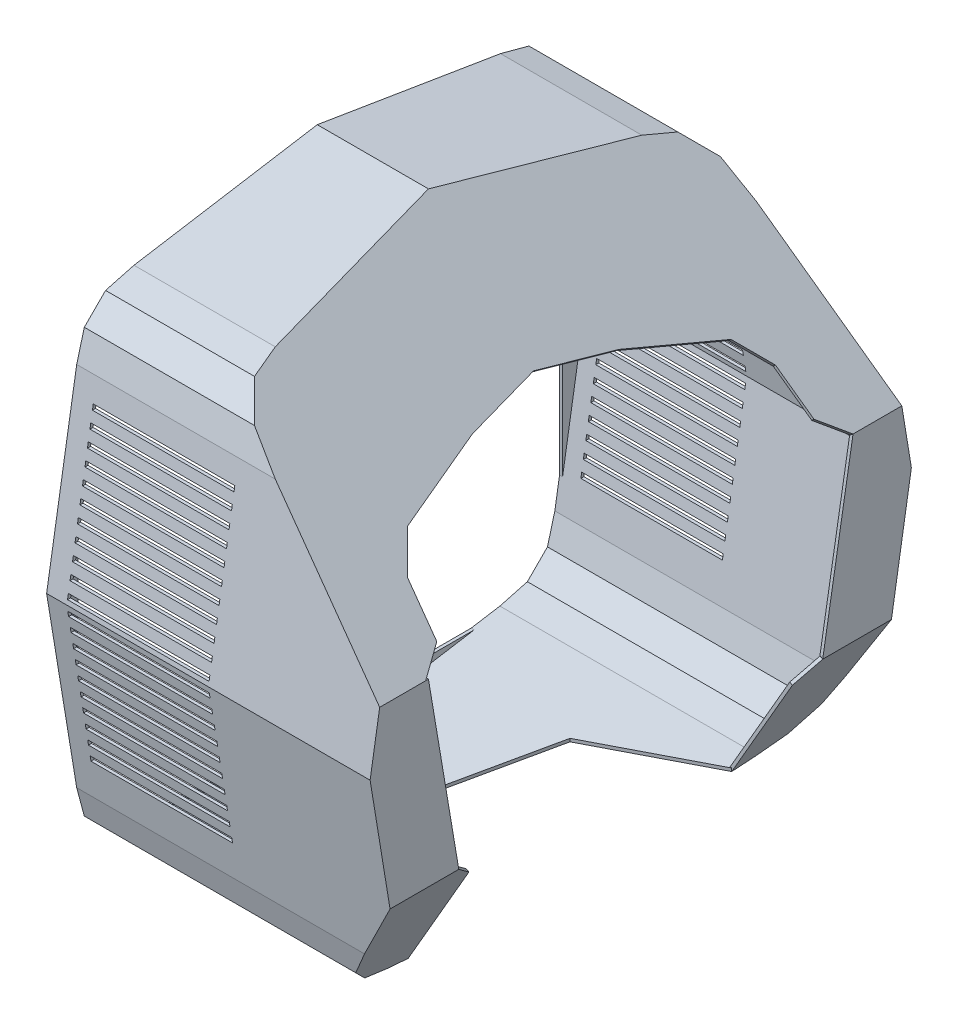
SolidWorks part; units mm, degrees
ref_plane "Plan de face" through (0, 0, 0) normal (0, 0, 1) x (1, 0, 0)
ref_plane "Plan de dessus" through (0, 0, 0) normal (0, 1, 0) x (1, 0, 0)
ref_plane "Plan de droite" through (0, 0, 0) normal (1, 0, 0) x (0, 0, -1)
sketch "Esquisse1" plane through (0, 0, 0) normal (1, 0, 0) x (0, 0, -1)
  line L0 (0, 0) -> (-210, 0) construction
  line L1 (0, 0) -> (0, -210) construction
  line L2 (40, -130) -> (40, -126.3181)
  line L3 (-40, -130) -> (40, -130) construction
  line L4 (-40, -130) -> (-40, -170)
  line L5 (-40, -170) -> (40, -170)
  line L6 (40, -130) -> (40, -170)
  line L7 (-40, -130) -> (-40, -126.3181)
  line L8 (40, 130) -> (40, 126.3181)
  line L9 (-40, 130) -> (-40, 126.3181)
  line L10 (-40, 130) -> (-40, 170)
  line L11 (-40, 130) -> (40, 130) construction
  line L12 (40, 130) -> (40, 170)
  line L13 (-40, 170) -> (40, 170)
  circle A0 centre (0, 0) radius 210
  circle A1 centre (0, 0) radius 147.5 construction
  circle A2 centre (-147.5, 0) radius 6.75
  arc A3 (40, -126.3181) -> (40, 126.3181) centre (0, 0) ccw
  circle A4 centre (-142.0303, 39.795) radius 6.75
  circle A5 centre (-126.0269, 76.6386) radius 6.75
  circle A6 centre (-100.6766, 107.7983) radius 6.75
  circle A7 centre (-67.8596, 130.9631) radius 6.75
  circle A8 centre (-30.0098, 144.4149) radius 6.75 construction
  circle A9 centre (10.0658, 147.1561) radius 6.75 construction
  circle A10 centre (49.3947, 138.9835) radius 6.75
  circle A11 centre (85.0603, 120.5031) radius 6.75
  circle A12 centre (114.4174, 93.0855) radius 6.75
  circle A13 centre (135.2887, 58.7642) radius 6.75
  circle A14 centre (146.1262, 20.0846) radius 6.75
  circle A15 centre (146.1262, -20.0846) radius 6.75
  circle A16 centre (135.2887, -58.7642) radius 6.75
  circle A17 centre (114.4174, -93.0855) radius 6.75
  circle A18 centre (85.0603, -120.5031) radius 6.75
  circle A19 centre (49.3947, -138.9835) radius 6.75
  circle A20 centre (10.0658, -147.1561) radius 6.75 construction
  circle A21 centre (-30.0098, -144.4149) radius 6.75 construction
  circle A22 centre (-67.8596, -130.9631) radius 6.75
  circle A23 centre (-100.6766, -107.7983) radius 6.75
  circle A24 centre (-126.0269, -76.6386) radius 6.75
  circle A25 centre (-142.0303, -39.795) radius 6.75
  arc A28 (-40, 126.3181) -> (-40, -126.3181) centre (0, 0) ccw
  point P55 (0, 0)
  point P59 (0, -130)
  point P60 (-130, 0)
  dimension "D1" = 147.5
  dimension "D2" = 13.5
  dimension "D3" = 265
  dimension "D5" = 420
  dimension "D6" = 40
  dimension "D9" = 132.5
  dimension "D7" = 80
  dimension "D8" = 130
  dimension "D4" = 23
extrude "Boss.-Extru.1" add sketch "Esquisse1" along normal blind 10
sketch "Esquisse2" plane through (0, 0, 0) normal (-1, 0, 0) x (0, 0, 1)
  line L0 (-180.6658, -180.6658) -> (-218.1424, -143.1891) construction
  line L1 (-180.6658, -180.6658) -> (-210.0107, -210.0107) construction
  line L2 (0, 0) -> (0, -255.5) construction
  line L3 (0, 0) -> (-180.6658, -180.6658) construction
  line L4 (-80.9762, -193.7598) -> (-127.4885, -240.2721)
  line L5 (240.2721, -127.4885) -> (269.6802, -156.8967)
  line L6 (-240.2721, -127.4885) -> (-193.7598, -80.9762)
  line L7 (-220.6173, -220.6173) -> (-210.0107, -210.0107) construction
  line L8 (-127.4885, 240.2721) -> (-80.9762, 193.7598)
  line L9 (240.2721, 127.4885) -> (269.6802, 156.8967)
  line L10 (-193.7598, 80.9762) -> (-240.2721, 127.4885)
  line L11 (240.2721, 127.4885) -> (193.7598, 80.9762)
  line L12 (127.4885, 240.2721) -> (156.8967, 269.6802)
  line L13 (80.9762, 193.7598) -> (127.4885, 240.2721)
  line L14 (127.4885, -240.2721) -> (80.3433, -193.1268)
  line L15 (127.4885, -240.2721) -> (156.8967, -269.6802)
  line L16 (193.7598, -80.9762) -> (240.2721, -127.4885)
  line L17 (-127.4885, 240.2721) -> (-156.8967, 269.6802)
  line L18 (-240.2721, 127.4885) -> (-269.6802, 156.8967)
  line L19 (-127.4885, -240.2721) -> (-156.8967, -269.6802)
  line L20 (-240.2721, -127.4885) -> (-269.6802, -156.8967)
  circle A0 centre (0, 0) radius 213 construction
  circle A1 centre (0, 0) radius 255.5 construction
  circle A2 centre (-180.6658, -180.6658) radius 42.5 construction
  circle A3 centre (-180.6658, -180.6658) radius 41.5
  circle A4 centre (-218.1424, -143.1891) radius 6.75
  circle A5 centre (-143.1891, -218.1424) radius 6.75
  circle A6 centre (0, 0) radius 210 construction
  arc A7 (-80.9762, -193.7598) -> (-193.7598, -80.9762) centre (0, 0) cw
  arc A8 (-193.7598, 80.9762) -> (-80.9762, 193.7598) centre (0, 0) cw
  circle A9 centre (-218.1424, 143.1891) radius 6.75
  circle A10 centre (-180.6658, 180.6658) radius 41.5
  circle A11 centre (-143.1891, 218.1424) radius 6.75
  arc A12 (80.9762, 193.7598) -> (193.7598, 80.9762) centre (0, 0) cw
  circle A13 centre (143.1891, 218.1424) radius 6.75
  circle A14 centre (180.6658, 180.6658) radius 41.5
  circle A15 centre (218.1424, 143.1891) radius 6.75
  arc A16 (193.7598, -80.9762) -> (80.9762, -193.7598) centre (0, 0) cw
  circle A17 centre (218.1424, -143.1891) radius 6.75
  circle A18 centre (180.6658, -180.6658) radius 41.5
  circle A19 centre (143.1891, -218.1424) radius 6.75
  circle A20 centre (0, 0) radius 312 construction
  arc A21 (240.2721, -127.4885) -> (240.2721, 127.4885) centre (0, 0) ccw construction
  arc A22 (-240.2721, 127.4885) -> (-240.2721, -127.4885) centre (0, 0) ccw construction
  arc A23 (127.4885, 240.2721) -> (-127.4885, 240.2721) centre (0, 0) ccw construction
  arc A24 (156.8967, -269.6802) -> (269.6802, -156.8967) centre (0, 0) ccw
  arc A25 (269.6802, 156.8967) -> (156.8967, 269.6802) centre (0, 0) ccw
  arc A26 (-127.4885, -240.2721) -> (127.4885, -240.2721) centre (0, 0) ccw construction
  arc A27 (-156.8967, 269.6802) -> (-269.6802, 156.8967) centre (0, 0) ccw
  arc A28 (-156.8967, -269.6802) -> (-269.6802, -156.8967) centre (0, 0) cw
  point P57 (0, 0)
  circle M11 centre (0, 0) radius 210
  dimension "D1" = 426
  dimension "D2" = 85
  dimension "D3" = 83
  dimension "D4" = 13.5
  dimension "D10" = 40
  dimension "D7" = 624
  dimension "D5" = 53
  dimension "D6" = 45
  dimension "D8" = 26.75
  dimension "D11" = 159.5
  dimension "D9" = 4
extrude "Boss.-Extru.2" add sketch "Esquisse2" against normal blind 10 contours A20 A26 L4 L6 A22 L10 L8 A23 L13 L11 A21 L16 L14 A17 A15 A14 A9 A3 A4 A5 A10 A11 A13 A18 A19 M11 | L9 A25 L12 L13 L11 A15 A14 A13 M11 | L17 A27 L18 L10 L8 A9 A10 A11 M11 | A28 L19 L4 L6 L20 A5 A4 A3 M11
sketch "Esquisse3" plane through (10, 0, 0) normal (1, 0, 0) x (0, 0, -1)
  line L0 (-156.8967, -269.6802) -> (156.8967, -269.6802)
  line L1 (156.8967, -269.6802) -> (126.8967, -239.6802)
  line L2 (-80.9762, -193.7598) -> (-156.8967, -269.6802) construction
  line L3 (126.8967, -239.6802) -> (-126.8967, -239.6802)
  line L4 (-193.7598, 80.9762) -> (-269.6802, 156.8967) construction
  line L5 (-126.8967, -239.6802) -> (-156.8967, -269.6802)
  line L6 (-269.6802, -156.8967) -> (-269.6802, 156.8967)
  line L7 (-269.6802, 156.8967) -> (-239.6802, 126.8967)
  line L8 (80.9762, 193.7598) -> (156.8967, 269.6802) construction
  line L9 (-239.6802, 126.8967) -> (-239.6802, -126.8967)
  line L11 (-239.6802, -126.8967) -> (-269.6802, -156.8967)
  line L12 (-156.8967, 269.6802) -> (156.8967, 269.6802)
  line L13 (156.8967, 269.6802) -> (126.8967, 239.6802)
  line L15 (126.8967, 239.6802) -> (-126.8967, 239.6802)
  line L17 (-126.8967, 239.6802) -> (-156.8967, 269.6802)
  line L18 (269.6802, 156.8967) -> (269.6802, -156.8967)
  line L19 (269.6802, -156.8967) -> (239.6802, -126.8967)
  line L21 (239.6802, -126.8967) -> (239.6802, 126.8967)
  line L23 (239.6802, 126.8967) -> (269.6802, 156.8967)
  line L24 (193.7598, 80.9762) -> (269.6802, 156.8967) construction
  dimension "D1" = 30
extrude "Boss.-Extru.3" add sketch "Esquisse3" against normal up to surface (10 mm away) up to face at (0, -76.6386, 119.2769)
fillet "Congé1" radius 20 16 edges at (5, -80.9762, 193.7598) (5, 193.7598, -80.9762) (5, -193.7598, 80.9762) (5, 80.9762, -193.7598) (5, -80.9762, -193.7598) (5, 80.9762, 193.7598) (5, -193.7598, -80.9762) (5, 193.7598, 80.9762) (5, -239.6802, 126.8967) (5, -239.6802, -126.8967) (5, -126.8967, -239.6802) (5, 126.8967, -239.6802) (5, 239.6802, -126.8967) (5, 239.6802, 126.8967) (5, 126.8967, 239.6802) (5, -126.8967, 239.6802)
sketch "Esquisse4" plane through (10, 0, 0) normal (1, 0, 0) x (0, 0, -1)
  line L0 (180.6658, 235.0178) -> (180.6658, 126.3138) construction
  line L1 (227.736, 207.8418) -> (207.8418, 227.736)
  line L2 (207.8418, 227.736) -> (180.6658, 235.0178)
  line L3 (180.6658, 235.0178) -> (153.4898, 227.736) construction
  line L4 (153.4898, 227.736) -> (133.5956, 207.8418) construction
  line L5 (133.5956, 207.8418) -> (126.3138, 180.6658) construction
  line L6 (126.3138, 180.6658) -> (133.5956, 153.4898) construction
  line L7 (133.5956, 153.4898) -> (153.4898, 133.5956) construction
  line L8 (153.4898, 133.5956) -> (180.6658, 126.3138) construction
  line L9 (180.6658, 126.3138) -> (207.8418, 133.5956) construction
  line L10 (207.8418, 133.5956) -> (227.736, 153.4898) construction
  line L11 (227.736, 153.4898) -> (235.0178, 180.6658) construction
  line L12 (235.0178, 180.6658) -> (227.736, 207.8418)
  line L13 (0, 0) -> (269.6802, 0) construction
  line L14 (269.6802, -156.8967) -> (269.6802, 156.8967) construction
  line L15 (0, 0) -> (0, 269.6802) construction
  line L16 (156.8967, 269.6802) -> (-156.8967, 269.6802) construction
  line L17 (180.6658, 235.0178) -> (0, 264.6802)
  line L18 (235.0178, 180.6658) -> (264.6802, 0)
  line L19 (180.6658, -235.0178) -> (0, -264.6802)
  line L20 (180.6658, -235.0178) -> (207.8418, -227.736)
  line L21 (207.8418, -227.736) -> (227.736, -207.8418)
  line L22 (227.736, -207.8418) -> (235.0178, -180.6658)
  line L23 (235.0178, -180.6658) -> (264.6802, 0)
  line L24 (-235.0178, -180.6658) -> (-264.6802, 0)
  line L25 (-235.0178, -180.6658) -> (-227.736, -207.8418)
  line L26 (-227.736, -207.8418) -> (-207.8418, -227.736)
  line L27 (-207.8418, -227.736) -> (-180.6658, -235.0178)
  line L28 (-180.6658, -235.0178) -> (0, -264.6802)
  line L29 (-180.6658, 235.0178) -> (0, 264.6802)
  line L30 (-180.6658, 235.0178) -> (-207.8418, 227.736)
  line L31 (-207.8418, 227.736) -> (-227.736, 207.8418)
  line L32 (-227.736, 207.8418) -> (-235.0178, 180.6658)
  line L33 (-235.0178, 180.6658) -> (-264.6802, 0)
  line L34 (-237.9541, -181.2986) -> (-267.7204, 0)
  line L35 (-237.9541, 181.2986) -> (-267.7204, 0)
  line L36 (-230.4257, 209.3947) -> (-237.9541, 181.2986)
  line L37 (-209.3947, 230.4257) -> (-230.4257, 209.3947)
  line L38 (-181.2986, 237.9541) -> (-209.3947, 230.4257)
  line L39 (-181.2986, 237.9541) -> (0, 267.7204)
  line L40 (181.2986, 237.9541) -> (0, 267.7204)
  line L41 (209.3947, 230.4257) -> (181.2986, 237.9541)
  line L42 (230.4257, 209.3947) -> (209.3947, 230.4257)
  line L43 (237.9541, 181.2986) -> (230.4257, 209.3947)
  line L44 (237.9541, 181.2986) -> (267.7204, 0)
  line L45 (237.9541, -181.2986) -> (267.7204, 0)
  line L46 (230.4257, -209.3947) -> (237.9541, -181.2986)
  line L47 (209.3947, -230.4257) -> (230.4257, -209.3947)
  line L48 (181.2986, -237.9541) -> (209.3947, -230.4257)
  line L49 (181.2986, -237.9541) -> (0, -267.7204)
  line L50 (-181.2986, -237.9541) -> (0, -267.7204)
  line L51 (-209.3947, -230.4257) -> (-181.2986, -237.9541)
  line L52 (-230.4257, -209.3947) -> (-209.3947, -230.4257)
  line L53 (-237.9541, -181.2986) -> (-230.4257, -209.3947)
  circle A0 centre (180.6658, 180.6658) radius 52.5 construction
  circle A1 centre (180.6658, -180.6658) radius 52.5 construction
  circle A2 centre (-180.6658, -180.6658) radius 52.5 construction
  circle A3 centre (-180.6658, 180.6658) radius 52.5 construction
  circle A4 centre (180.6658, 180.6658) radius 52.5 construction
  point P12 (0, 0)
  point P55 (0, 0)
  dimension "D1" = 105
  dimension "D3" = 5
  dimension "D4" = 5
  dimension "D6" = 3
  dimension "D2" = 4
  dimension "D5" = 4
extrude "Boss.-Extru.4" add sketch "Esquisse4" along normal blind 320
sketch "Esquisse5" plane through (10, 0, 0) normal (1, 0, 0) x (0, 0, -1)
  line L0 (-239.6802, 78.6124) -> (-239.6802, -78.6124)
  line L1 (-239.6802, -78.6124) -> (-239.6802, 78.6124) construction
  line L2 (-239.6802, -78.6124) -> (-239.6802, -152.2681)
  line L3 (-264.6802, 0) -> (-235.0178, -180.6658) construction
  line L4 (-239.6802, -152.2681) -> (-264.6802, 0)
  line L5 (-264.6802, 0) -> (-239.6802, 152.2681)
  line L6 (-235.0178, 180.6658) -> (-264.6802, 0) construction
  line L7 (-239.6802, 152.2681) -> (-239.6802, 78.6124)
  line L8 (78.6124, 239.6802) -> (-78.6124, 239.6802)
  line L9 (-78.6124, 239.6802) -> (-152.2681, 239.6802)
  line L10 (-152.2681, 239.6802) -> (0, 264.6802)
  line L11 (0, 264.6802) -> (152.2681, 239.6802)
  line L12 (152.2681, 239.6802) -> (78.6124, 239.6802)
  line L13 (239.6802, -78.6124) -> (239.6802, 78.6124)
  line L14 (239.6802, 78.6124) -> (239.6802, 152.2681)
  line L15 (239.6802, 152.2681) -> (264.6802, 0)
  line L16 (264.6802, 0) -> (239.6802, -152.2681)
  line L17 (239.6802, -152.2681) -> (239.6802, -78.6124)
  line L18 (-78.6124, -239.6802) -> (78.6124, -239.6802)
  line L19 (78.6124, -239.6802) -> (152.2681, -239.6802)
  line L20 (152.2681, -239.6802) -> (0, -264.6802)
  line L21 (0, -264.6802) -> (-152.2681, -239.6802)
  line L22 (-152.2681, -239.6802) -> (-78.6124, -239.6802)
  arc A0 (-239.6802, -78.6124) -> (-205.5381, -92.7546) centre (-219.6802, -78.6124) ccw construction
  point P34 (0, 0)
  dimension "D1" = 4
extrude "Boss.-Extru.5" add sketch "Esquisse5" along normal blind 3
sketch "Esquisse6" plane through (0, 269.6802, 0) normal (0, 1, 0) x (1, 0, 0)
  line L1 (-73.5539, 269.6802) -> (10, 269.6802)
  line L2 (-73.5539, 269.6802) -> (-73.5539, -269.6802)
  line L3 (-73.5539, -269.6802) -> (10, -269.6802)
  line L4 (10, 269.6802) -> (10, -269.6802)
extrude "Enlèv. mat.-Extru.1" cut sketch "Esquisse6" against normal through all
sketch "Esquisse7" plane through (0, 0, 0) normal (0, 1, 0) x (1, 0, 0)
  line L1 (260, 160) -> (146.8629, 113.1371)
  line L2 (146.8629, 113.1371) -> (100, 0)
  line L3 (100, 0) -> (146.8629, -113.1371)
  line L4 (146.8629, -113.1371) -> (260, -160)
  line L5 (260, -160) -> (373.1371, -113.1371) construction
  line L6 (373.1371, -113.1371) -> (420, 0) construction
  line L7 (420, 0) -> (373.1371, 113.1371) construction
  line L8 (373.1371, 113.1371) -> (260, 160) construction
  line L9 (100, 0) -> (420, 0) construction
  line L10 (260, 160) -> (420, 160)
  line L11 (420, 160) -> (420, 0)
  line L12 (420, 0) -> (420, -160)
  line L13 (420, -160) -> (260, -160)
  line L15 (260, 0) -> (0, 0) construction
  line L16 (330, 0) -> (330, -181.2986) construction
  circle A0 centre (260, 0) radius 147.8207 construction
  dimension "D1" = 160
  dimension "D2" = 90
extrude "Enlèv. mat.-Extru.2" cut sketch "Esquisse7" against normal through all
sketch "Esquisse8" plane through (0, 0, 0) normal (0, 0, 1) x (1, 0, 0)
  line L0 (170, 267.7204) -> (170, 159.2986) construction
  line L1 (170, 159.2986) -> (30, 159.2986)
  line L2 (170, 159.2986) -> (170, 154.2986)
  line L3 (170, 154.2986) -> (30, 154.2986)
  line L4 (30, 159.2986) -> (30, 154.2986)
  line L5 (330, 267.7204) -> (10, 267.7204) construction
  line L6 (30, 267.7204) -> (30, 159.2986) construction
  line L7 (330, 181.2986) -> (330, 0) construction
  line L8 (10, 181.2986) -> (10, 0) construction
  line L9 (330, 181.2986) -> (10, 181.2986) construction
  line L10 (170, 144.2986) -> (30, 144.2986)
  line L11 (170, 144.2986) -> (170, 139.2986)
  line L12 (170, 139.2986) -> (30, 139.2986)
  line L13 (30, 144.2986) -> (30, 139.2986)
  line L14 (170, 129.2986) -> (30, 129.2986)
  line L15 (170, 129.2986) -> (170, 124.2986)
  line L16 (170, 124.2986) -> (30, 124.2986)
  line L17 (30, 129.2986) -> (30, 124.2986)
  line L18 (170, 114.2986) -> (30, 114.2986)
  line L19 (170, 114.2986) -> (170, 109.2986)
  line L20 (170, 109.2986) -> (30, 109.2986)
  line L21 (30, 114.2986) -> (30, 109.2986)
  line L22 (170, 99.2986) -> (30, 99.2986)
  line L23 (170, 99.2986) -> (170, 94.2986)
  line L24 (170, 94.2986) -> (30, 94.2986)
  line L25 (30, 99.2986) -> (30, 94.2986)
  line L26 (170, 84.2986) -> (30, 84.2986)
  line L27 (170, 84.2986) -> (170, 79.2986)
  line L28 (170, 79.2986) -> (30, 79.2986)
  line L29 (30, 84.2986) -> (30, 79.2986)
  line L30 (170, 69.2986) -> (30, 69.2986)
  line L31 (170, 69.2986) -> (170, 64.2986)
  line L32 (170, 64.2986) -> (30, 64.2986)
  line L33 (30, 69.2986) -> (30, 64.2986)
  line L34 (170, 54.2986) -> (30, 54.2986)
  line L35 (170, 54.2986) -> (170, 49.2986)
  line L36 (170, 49.2986) -> (30, 49.2986)
  line L37 (30, 54.2986) -> (30, 49.2986)
  line L38 (170, 39.2986) -> (30, 39.2986)
  line L39 (170, 39.2986) -> (170, 34.2986)
  line L40 (170, 34.2986) -> (30, 34.2986)
  line L41 (30, 39.2986) -> (30, 34.2986)
  line L42 (170, 24.2986) -> (30, 24.2986)
  line L43 (170, 24.2986) -> (170, 19.2986)
  line L44 (170, 19.2986) -> (30, 19.2986)
  line L45 (30, 24.2986) -> (30, 19.2986)
  line L46 (170, 9.2986) -> (30, 9.2986)
  line L47 (170, 9.2986) -> (170, 4.2986)
  line L48 (170, 4.2986) -> (30, 4.2986)
  line L49 (30, 9.2986) -> (30, 4.2986)
  line L50 (170, -5.7014) -> (30, -5.7014)
  line L51 (170, -5.7014) -> (170, -10.7014)
  line L52 (170, -10.7014) -> (30, -10.7014)
  line L53 (30, -5.7014) -> (30, -10.7014)
  line L54 (170, -20.7014) -> (30, -20.7014)
  line L55 (170, -20.7014) -> (170, -25.7014)
  line L56 (170, -25.7014) -> (30, -25.7014)
  line L57 (30, -20.7014) -> (30, -25.7014)
  line L58 (170, -35.7014) -> (30, -35.7014)
  line L59 (170, -35.7014) -> (170, -40.7014)
  line L60 (170, -40.7014) -> (30, -40.7014)
  line L61 (30, -35.7014) -> (30, -40.7014)
  line L62 (170, -50.7014) -> (30, -50.7014)
  line L63 (170, -50.7014) -> (170, -55.7014)
  line L64 (170, -55.7014) -> (30, -55.7014)
  line L65 (30, -50.7014) -> (30, -55.7014)
  line L66 (170, -65.7014) -> (30, -65.7014)
  line L67 (170, -65.7014) -> (170, -70.7014)
  line L68 (170, -70.7014) -> (30, -70.7014)
  line L69 (30, -65.7014) -> (30, -70.7014)
  line L70 (30, 154.2986) -> (30, 144.2986) construction
  line L71 (170, -80.7014) -> (30, -80.7014)
  line L72 (170, -80.7014) -> (170, -85.7014)
  line L73 (170, -85.7014) -> (30, -85.7014)
  line L74 (30, -80.7014) -> (30, -85.7014)
  line L75 (170, -95.7014) -> (30, -95.7014)
  line L76 (170, -95.7014) -> (170, -100.7014)
  line L77 (170, -100.7014) -> (30, -100.7014)
  line L78 (30, -95.7014) -> (30, -100.7014)
  line L79 (170, -110.7014) -> (30, -110.7014)
  line L80 (170, -110.7014) -> (170, -115.7014)
  line L81 (170, -115.7014) -> (30, -115.7014)
  line L82 (30, -110.7014) -> (30, -115.7014)
  line L83 (170, -125.7014) -> (30, -125.7014)
  line L84 (170, -125.7014) -> (170, -130.7014)
  line L85 (170, -130.7014) -> (30, -130.7014)
  line L86 (30, -125.7014) -> (30, -130.7014)
  line L87 (170, -140.7014) -> (30, -140.7014)
  line L88 (170, -140.7014) -> (170, -145.7014)
  line L89 (170, -145.7014) -> (30, -145.7014)
  line L90 (30, -140.7014) -> (30, -145.7014)
  dimension "D1" = 160
  dimension "D2" = 20
  dimension "D3" = 5
  dimension "D4" = 22
  dimension "D6" = 10
  dimension "D5" = 21
extrude "Enlèv. mat.-Extru.3" cut sketch "Esquisse8" against normal through all both and the other way through all
sketch "Esquisse9" plane through (0, 0, 0) normal (0, 0, 1) x (1, 0, 0)
  line L0 (330, 57.7204) -> (120, 267.7204)
  line L1 (330, 181.2986) -> (330, 0) construction
  line L3 (330, 267.7204) -> (10, 267.7204) construction
  line L4 (330, 57.7204) -> (330, 267.7204)
  line L5 (330, 267.7204) -> (120, 267.7204)
  line L6 (330, -120.2074) -> (260, -241.4509)
  line L7 (330, 0) -> (330, -181.2986) construction
  line L8 (260, -241.4509) -> (330, -241.4509)
  line L9 (330, -241.4509) -> (330, -120.2074)
  dimension "D1" = 45
  dimension "D2" = 210
  dimension "D3" = 30
extrude "Enlèv. mat.-Extru.4" cut sketch "Esquisse9" against normal through all both and the other way through all
sketch "Esquisse10" plane through (193.8602, 193.8602, 0) normal (0.7071, 0.7071, 0) x (0, 0, -1)
  line L0 (258.2436, -192.5308) -> (-258.2436, -192.5308)
  line L1 (-258.2436, -192.5308) -> (-230.4257, 21.9691)
  line L2 (-230.4257, 21.9691) -> (-209.3947, 51.7115)
  line L3 (-209.3947, 51.7115) -> (-181.2986, 62.3581)
  line L4 (-181.2986, 62.3581) -> (0, 104.4541)
  line L5 (0, 104.4541) -> (181.2986, 62.3581)
  line L6 (181.2986, 62.3581) -> (209.3947, 51.7115)
  line L7 (209.3947, 51.7115) -> (230.4257, 21.9691)
  line L8 (230.4257, 21.9691) -> (237.9541, -17.7648)
  line L9 (237.9541, -17.7648) -> (258.2436, -192.5308)
extrude "Boss.-Extru.6" add sketch "Esquisse10" against normal blind 3
sketch "Esquisse11" plane through (193.8602, 193.8602, 0) normal (0.7071, 0.7071, 0) x (0, 0, -1)
  line L0 (0, -192.5308) -> (0, -42.5308) construction
  line L1 (-255.2035, -192.5308) -> (255.2035, -192.5308) construction
  line L2 (0, -42.5308) -> (72.438, -59.3502)
  line L3 (72.438, -59.3502) -> (160, -92.5308)
  line L4 (160, -92.5308) -> (182.003, -123.6477)
  line L5 (182.003, -123.6477) -> (190, -192.5308)
  line L6 (237.9541, -17.7648) -> (258.2436, -192.5308) construction
  line L7 (0, 104.4541) -> (181.2986, 62.3581) construction
  line L8 (181.2986, 62.3581) -> (209.3947, 51.7115) construction
  line L9 (209.3947, 51.7115) -> (230.4257, 21.9691) construction
  line L10 (190, -192.5308) -> (-190, -192.5308)
  line L11 (160, -92.5308) -> (0, -92.5308) construction
  line L12 (160, -92.5308) -> (160, -192.5308) construction
  line L13 (-182.003, -123.6477) -> (-190, -192.5308)
  line L14 (-160, -92.5308) -> (-182.003, -123.6477)
  line L15 (-72.438, -59.3502) -> (-160, -92.5308)
  line L16 (0, -42.5308) -> (-72.438, -59.3502)
  dimension "D1" = 150
  dimension "D2" = 190
  dimension "D3" = 100
  dimension "D4" = 160
extrude "Enlèv. mat.-Extru.5" cut sketch "Esquisse11" against normal blind 3
sketch "Esquisse12" plane through (299.5513, -172.946, 0) normal (0.866, -0.5, 0) x (0, 0, -1)
  line L0 (160, -79.1026) -> (160, -75.5922)
  line L1 (160, -75.5922) -> (160, 60.8974)
  line L2 (160, 60.8974) -> (244.9441, 60.8974)
  line L3 (244.9441, 60.8974) -> (247.9843, 60.8974)
  line L4 (247.9843, 60.8974) -> (237.9541, -9.6447)
  line L5 (237.9541, -9.6447) -> (230.4257, -42.0873)
  line L6 (230.4257, -42.0873) -> (209.3947, -66.3718)
  line L7 (209.3947, -66.3718) -> (181.2986, -75.0648)
  line L8 (181.2986, -75.0648) -> (160, -79.1026)
  line L9 (0, 0) -> (0, 291.8527) construction
  line L10 (-181.2986, -75.0648) -> (-160, -79.1026)
  line L11 (-209.3947, -66.3718) -> (-181.2986, -75.0648)
  line L12 (-230.4257, -42.0873) -> (-209.3947, -66.3718)
  line L13 (-237.9541, -9.6447) -> (-230.4257, -42.0873)
  line L14 (-247.9843, 60.8974) -> (-237.9541, -9.6447)
  line L15 (-244.9441, 60.8974) -> (-247.9843, 60.8974)
  line L16 (-160, 60.8974) -> (-244.9441, 60.8974)
  line L17 (-160, -75.5922) -> (-160, 60.8974)
  line L18 (-160, -79.1026) -> (-160, -75.5922)
extrude "Boss.-Extru.7" add sketch "Esquisse12" against normal blind 3
chamfer "Chanfrein1" distance 20 angle 45 4 edges at (328.9393, 56.6597, -190) (328.9393, 56.6597, 190) (328.701, -119.4574, 160) (328.701, -119.4574, -160)
sketch "Esquisse13" plane through (330, 0, 0) normal (1, 0, 0) x (0, 0, -1)
  line L0 (258.2436, 57.7204) -> (267.7204, 0)
  line L1 (267.7204, 0) -> (247.9843, -120.2074)
  line L2 (247.9843, -120.2074) -> (180, -120.2074)
  line L3 (180, -120.2074) -> (210, 57.7204)
  line L4 (210, 57.7204) -> (258.2436, 57.7204)
  line L5 (0, 0) -> (0, -124.9474) construction
  line L6 (-210, 57.7204) -> (-258.2436, 57.7204)
  line L7 (-180, -120.2074) -> (-210, 57.7204)
  line L8 (-247.9843, -120.2074) -> (-180, -120.2074)
  line L9 (-267.7204, 0) -> (-247.9843, -120.2074)
  line L10 (-258.2436, 57.7204) -> (-267.7204, 0)
extrude "Boss.-Extru.8" add sketch "Esquisse13" against normal blind 3
